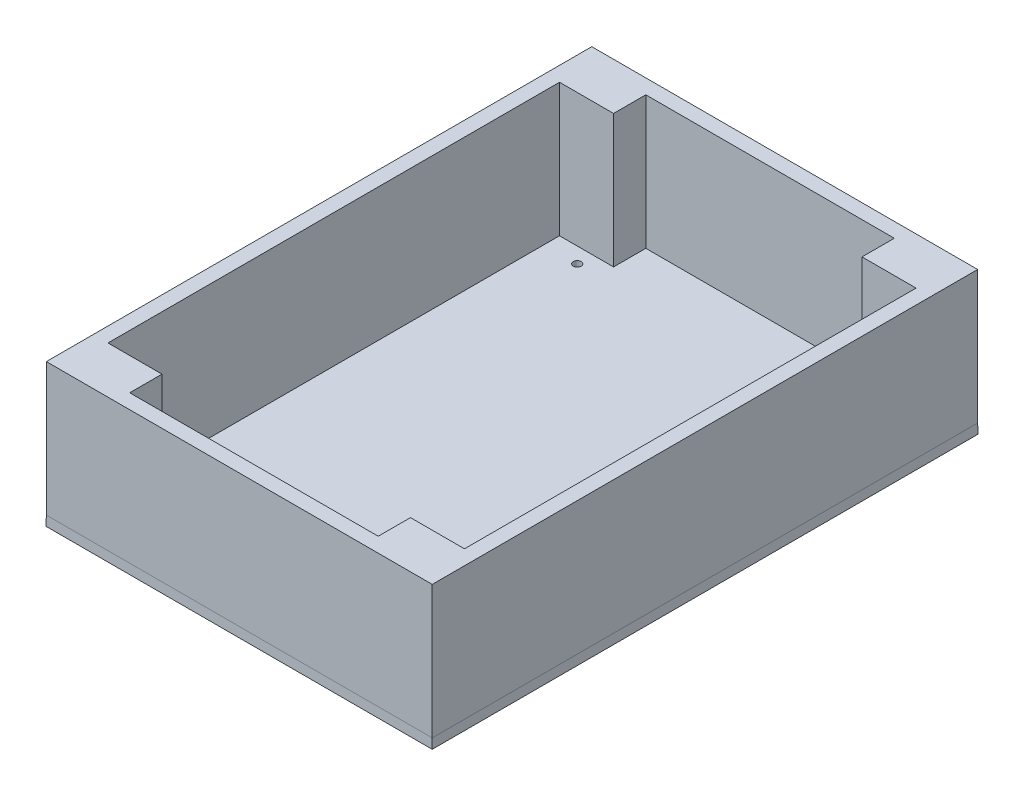
SolidWorks part; units mm, degrees
ref_plane "Front Plane" through (0, 0, 0) normal (0, 0, 1) x (1, 0, 0)
ref_plane "Top Plane" through (0, 0, 0) normal (0, 1, 0) x (1, 0, 0)
ref_plane "Right Plane" through (0, 0, 0) normal (1, 0, 0) x (0, 0, -1)
sketch "Sketch1" plane through (0, 0, 0) normal (0, 1, 0) x (1, 0, 0)
  line L1 (60.5028, -85.4964) -> (-60.5028, -85.4964)
  line L2 (60.5028, -85.4964) -> (60.5028, 85.4964)
  line L3 (60.5028, 85.4964) -> (-60.5028, 85.4964)
  line L4 (-60.5028, -85.4964) -> (-60.5028, 85.4964)
  line L5 (60.5028, -85.4964) -> (-60.5028, 85.4964) construction
  line L6 (60.5028, 85.4964) -> (-60.5028, -85.4964) construction
  point P0 (0, 0)
  dimension "D1" = 121.0056
  dimension "D2" = 170.9928
extrude "Boss-Extrude1" add sketch "Sketch1" along normal blind 3.048 draft 1
sketch "Sketch2" plane through (0, 3.048, 0) normal (0, 1, 0) x (1, 0, 0)
  line L0 (-55.8522, 70.739) -> (-55.8522, -70.739)
  line L1 (-38.9255, -80.8458) -> (38.9255, -80.8458)
  line L2 (55.8522, -70.739) -> (55.8522, 70.739)
  line L3 (38.9255, 80.8458) -> (-38.9255, 80.8458)
  line L4 (-60.4496, 85.4432) -> (-60.4496, -85.4432)
  line L5 (-60.4496, -85.4432) -> (60.4496, -85.4432)
  line L6 (60.4496, -85.4432) -> (60.4496, 85.4432)
  line L7 (60.4496, 85.4432) -> (-60.4496, 85.4432)
  line L8 (-60.4496, 85.4432) -> (-60.4496, -85.4432)
  line L9 (-60.4496, -85.4432) -> (60.4496, -85.4432)
  line L10 (60.4496, -85.4432) -> (60.4496, 85.4432)
  line L11 (60.4496, 85.4432) -> (-60.4496, 85.4432)
  line L12 (38.9255, 80.8458) -> (38.9255, 70.739)
  line L13 (38.9255, 70.739) -> (55.8522, 70.739)
  line L14 (111.7044, 0) -> (0, 0) construction
  line L15 (0, 0) -> (0, -50000) construction
  line L16 (-38.9255, 70.739) -> (-55.8522, 70.739)
  line L17 (-38.9255, 80.8458) -> (-38.9255, 70.739)
  line L18 (-38.9255, -80.8458) -> (-38.9255, -70.739)
  line L19 (-38.9255, -70.739) -> (-55.8522, -70.739)
  line L20 (38.9255, -70.739) -> (55.8522, -70.739)
  line L21 (38.9255, -80.8458) -> (38.9255, -70.739)
  line L22 (-55.8522, 80.8458) -> (-55.8522, -80.8458) construction
  line L23 (55.8522, 80.8458) -> (-55.8522, 80.8458) construction
  line L24 (-55.8522, -80.8458) -> (55.8522, -80.8458) construction
  line L25 (55.8522, -80.8458) -> (55.8522, 80.8458) construction
  point P15 (55.8522, 0)
  point P18 (0, -85.4432)
  point P28 (47.3888, -70.739)
  dimension "D3" = 141.478
  dimension "D4" = 77.851
  dimension "D1" = 0
  dimension "D2" = 4.5974
extrude "Boss-Extrude2" add sketch "Sketch2" along normal blind 41.656
hole_wizard "M3 Tapped Hole1" positions "Sketch4" profile "Sketch5" tap size "M3" standard "ISO"
sketch "Sketch4" plane through (0, 3.048, 0) normal (0, 1, 0) x (1, 0, 0)
  line L0 (0, 0) -> (50000, 0) construction
  line L1 (55.8522, -70.739) -> (55.8522, 70.739) construction
  line L2 (0, 0) -> (0, 50000) construction
  line L3 (38.9255, 80.8458) -> (-38.9255, 80.8458) construction
  line L5 (45.466, -65.8876) -> (-45.466, -65.8876)
  line L6 (45.466, -65.8876) -> (45.466, 65.8876)
  line L7 (45.466, 65.8876) -> (-45.466, 65.8876)
  line L8 (-45.466, -65.8876) -> (-45.466, 65.8876)
  line L9 (45.466, -65.8876) -> (-45.466, 65.8876) construction
  line L10 (45.466, 65.8876) -> (-45.466, -65.8876) construction
  point P6 (55.8522, 0)
  point P11 (0, 80.8458)
  point P13 (-45.466, 65.8876)
  point P74 (45.466, -65.8876)
  point P75 (45.466, 65.8876)
  point P76 (-45.466, -65.8876)
  point P77 (0, 0)
  dimension "D1" = 90.932
  dimension "D2" = 131.7752
sketch "Sketch5" plane through (-45.466, 3.048, -65.8876) normal (1, 0, 0) x (0, 0, 1)
  line L0 (0, 0) -> (0, 5.5263)
  line L1 (0, 5.5263) -> (1.25, 4.7752)
  line L2 (1.25, 4.7752) -> (1.25, 0)
  line L5 (1.25, 0) -> (0, 0)
  line L10 (0, 5.5263) -> (-1.25, 4.7752) construction
  line L11 (0, -6.35) -> (0, 107.95) construction
  dimension "Tap Drill Dia." = 2.5
  dimension "Tap Drill Depth" = 4.7752
  dimension "Drill Angle" = 118
cosmetic thread "Hole Thread1" parameters "D1"=3.048, "D2"=3
cosmetic thread "Hole Thread2" parameters "D1"=3.048, "D2"=3
cosmetic thread "Hole Thread3" parameters "D1"=3.048, "D2"=3
cosmetic thread "Hole Thread4" parameters "D1"=3.048, "D2"=3
